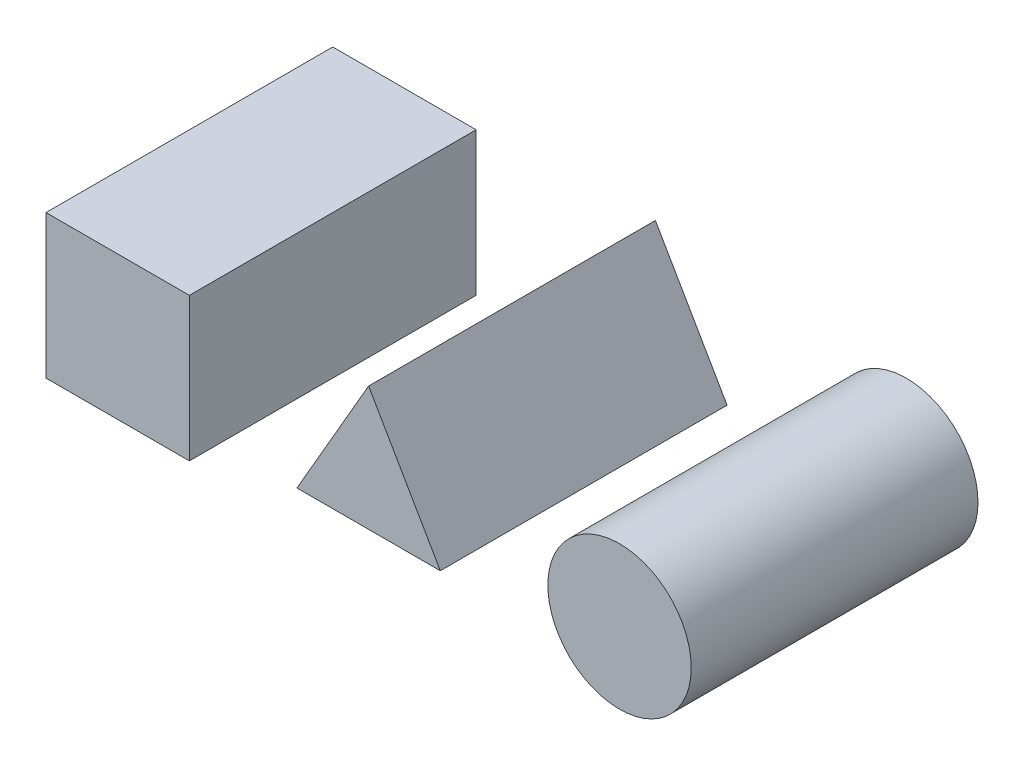
SolidWorks part; units mm, degrees
ref_plane "Front Plane" through (0, 0, 0) normal (0, 0, 1) x (1, 0, 0)
ref_plane "Top Plane" through (0, 0, 0) normal (0, 1, 0) x (1, 0, 0)
ref_plane "Right Plane" through (0, 0, 0) normal (1, 0, 0) x (0, 0, -1)
sketch "Sketch1" plane through (0, 0, 0) normal (0, 0, 1) x (1, 0, 0)
  line L0 (-120, 0) -> (120, 0) construction
  line L1 (-120, 57.5) -> (120, 57.5)
  line L2 (-120, 57.5) -> (-120, -57.5)
  line L3 (-120, -57.5) -> (120, -57.5)
  line L4 (120, 57.5) -> (120, -57.5)
  line L5 (0, 57.5) -> (0, -57.5) construction
  line L6 (-20, -11.547) -> (0, 23.094)
  line L7 (-90, 20) -> (-50, 20)
  line L8 (-90, 20) -> (-90, -20)
  line L9 (-90, -20) -> (-50, -20)
  line L10 (-50, 20) -> (-50, -20)
  line L11 (-90, 20) -> (-50, -20) construction
  line L12 (-90, -20) -> (-50, 20) construction
  line L14 (-1.3522, 0) -> (0, -1.3522)
  line L18 (0, 23.094) -> (20, -11.547)
  line L19 (20, -11.547) -> (-20, -11.547)
  line L20 (-20, -11.547) -> (10, 5.7735) construction
  line L21 (20, -11.547) -> (-10, 5.7735) construction
  line L22 (0, 23.094) -> (0, 0) construction
  circle A0 centre (70, 0) radius 20
  point P10 (-70, 0)
  point P20 (0, 0)
  point P27 (7.7505, -5.3087)
  point P28 (0, 0)
  dimension "D2" = 50
  dimension "cylinder" = 40
  dimension "D1" = 30
  dimension "square2" = 40
  dimension "square" = 40
  dimension "triangle3" = 40
  dimension "triangle2" = 40
  dimension "triangle" = 40
extrude "Boss-Extrude1" add sketch "Sketch1" along normal blind 80
